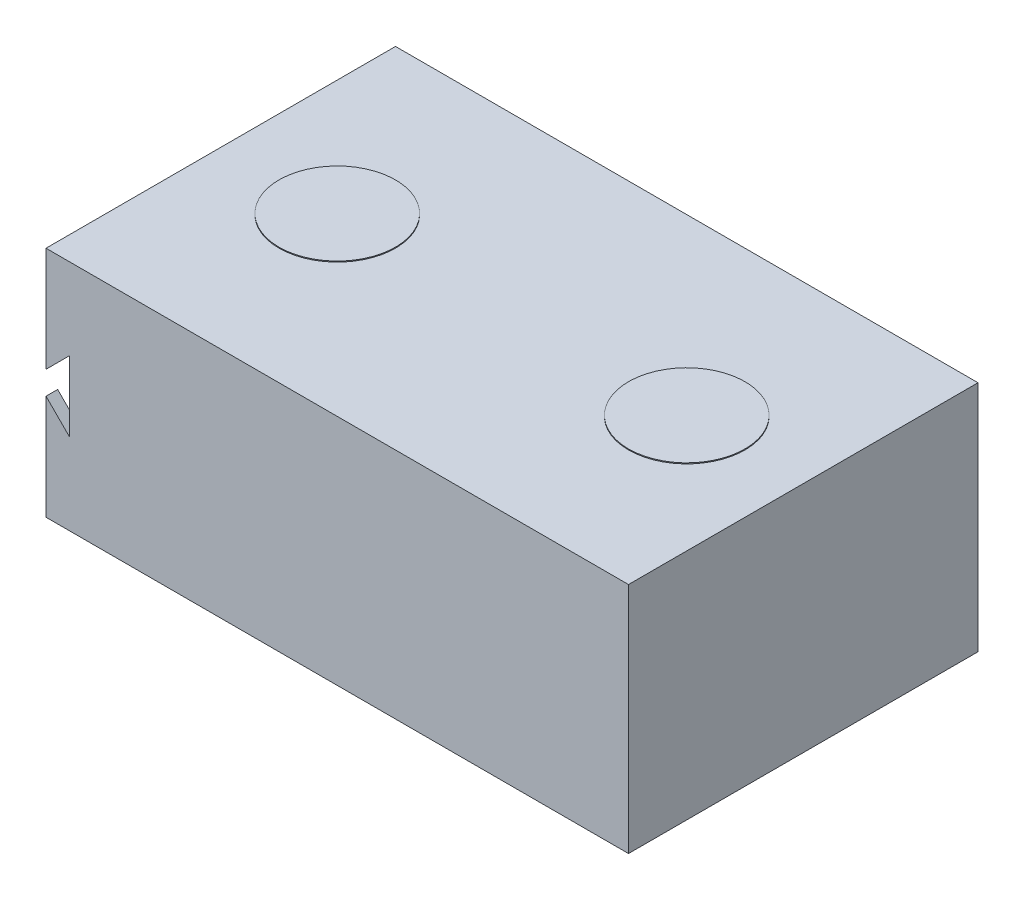
SolidWorks part; units mm, degrees
ref_plane "前视基准面" through (0, 0, 0) normal (0, 0, 1) x (1, 0, 0)
ref_plane "上视基准面" through (0, 0, 0) normal (0, 1, 0) x (1, 0, 0)
ref_plane "右视基准面" through (0, 0, 0) normal (1, 0, 0) x (0, 0, -1)
sketch "草图1" plane through (0, 0, 0) normal (0, 1, 0) x (1, 0, 0)
  line L0 (-123.5795, 64.1572) -> (126.4205, 64.1572)
  line L1 (-123.5795, 64.1572) -> (-123.5795, -85.8428)
  line L2 (126.4205, 64.1572) -> (126.4205, -85.8428)
  line L3 (-123.5795, -85.8428) -> (126.4205, -85.8428)
  dimension "D1" = 250
  dimension "D2" = 150
extrude "凸台-拉伸1" add sketch "草图1" along normal blind 100
sketch "草图2" plane through (0, 100, 0) normal (0, 1, 0) x (1, 0, 0)
  line L0 (126.4205, 64.1572) -> (-123.5795, 64.1572) construction
  line L1 (126.4205, -85.8428) -> (126.4205, 64.1572) construction
  circle A0 centre (76.4205, -10.8428) radius 25
  circle A1 centre (-73.5795, -10.8428) radius 25
  dimension "D1" = 50
  dimension "D4" = 50
  dimension "D6" = 150
  dimension "D2" = 75
  dimension "D3" = 50
  dimension "D5" = 75
extrude "凸台-拉伸2" add sketch "草图2" along normal blind 0.4
sketch "草图5" plane through (0, 0, 0) normal (0, -1, 0) x (1, 0, 0)
  line L0 (-123.5795, 80.8428) -> (121.4205, 80.8428)
  line L1 (-123.5795, 80.8428) -> (-123.5795, -59.1572)
  line L2 (121.4205, 80.8428) -> (121.4205, -59.1572)
  line L3 (-123.5795, -59.1572) -> (121.4205, -59.1572)
  line L4 (-123.5795, -64.1572) -> (-123.5795, 85.8428) construction
  line L5 (-123.5795, 85.8428) -> (126.4205, 85.8428) construction
  line L6 (126.4205, -64.1572) -> (-123.5795, -64.1572) construction
  line L7 (126.4205, 85.8428) -> (126.4205, -64.1572) construction
  dimension "D1" = 5
  dimension "D2" = 5
  dimension "D3" = 5
extrude "切除-拉伸1" cut sketch "草图5" against normal blind 95
sketch "草图7" plane through (0, 0, 85.8428) normal (0, 0, 1) x (1, 0, 0)
  line L0 (-123.5795, 55) -> (-113.5795, 55)
  line L1 (-123.5795, 55) -> (-123.5795, 45)
  line L2 (-113.5795, 55) -> (-113.5795, 45)
  line L3 (-123.5795, 45) -> (-113.5795, 45)
  line L4 (-123.5795, 100) -> (-123.5795, 0) construction
  line L5 (-123.5795, 100) -> (126.4205, 100) construction
  line L6 (-123.5795, 0) -> (126.4205, 0) construction
  point P10 (-113.5795, 50)
  dimension "D1" = 45
  dimension "D2" = 45
  dimension "D3" = 10
extrude "切除-拉伸2" cut sketch "草图7" against normal blind 5
sketch "草图9" plane through (0, 0, 85.8428) normal (0, 0, 1) x (1, 0, 0)
  line L0 (-123.5795, 55) -> (-113.5795, 65)
  line L1 (-113.5795, 65) -> (-113.5795, 55)
  line L2 (-113.5795, 55) -> (-123.5795, 55)
  line L3 (-123.5795, 45) -> (-113.5795, 45)
  line L4 (-113.5795, 45) -> (-113.5795, 35)
  line L5 (-113.5795, 35) -> (-123.5795, 45)
  dimension "D1" = 45
  dimension "D2" = 45
extrude "切除-拉伸3" cut sketch "草图9" against normal blind 5
sketch "草图10" plane through (0, 0, -64.1572) normal (0, 0, -1) x (-1, 0, 0)
  line L0 (123.5795, 55) -> (113.5795, 55)
  line L1 (123.5795, 55) -> (123.5795, 45)
  line L2 (113.5795, 55) -> (113.5795, 45)
  line L3 (123.5795, 45) -> (113.5795, 45)
  line L4 (123.5795, 100) -> (123.5795, 0) construction
  line L5 (-126.4205, 100) -> (123.5795, 100) construction
  line L6 (-126.4205, 0) -> (123.5795, 0) construction
  dimension "D1" = 45
  dimension "D2" = 45
  dimension "D3" = 10
extrude "切除-拉伸4" cut sketch "草图10" against normal blind 5
sketch "草图17" plane through (0, 0, -64.1572) normal (0, 0, -1) x (-1, 0, 0)
  line L0 (123.5795, 55) -> (113.5795, 65)
  line L1 (113.5795, 65) -> (113.5795, 55)
  line L2 (113.5795, 55) -> (123.5795, 55)
  line L3 (123.5795, 45) -> (113.5795, 35)
  line L5 (113.5795, 35) -> (113.5795, 45)
  line L6 (113.5795, 45) -> (123.5795, 45)
  dimension "D1" = 45
  dimension "D2" = 45
extrude "切除-拉伸6" cut sketch "草图17" against normal blind 5
